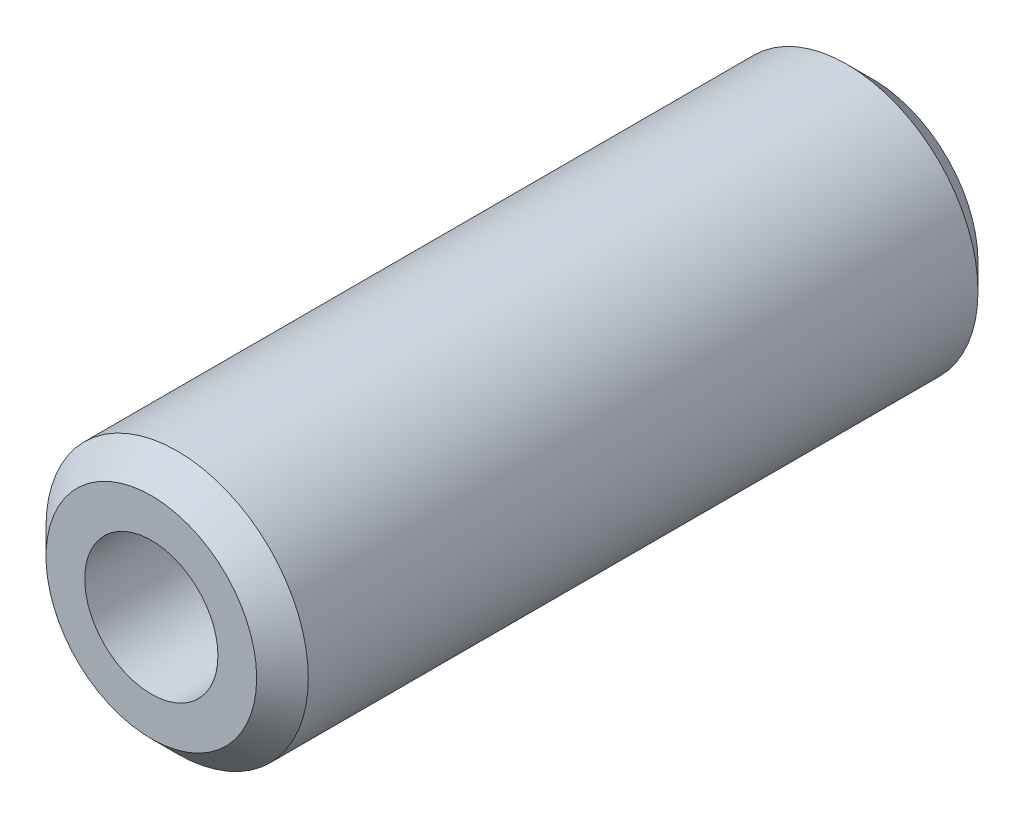
SolidWorks part; units mm, degrees
ref_plane "Front Plane" through (0, 0, 0) normal (0, 0, 1) x (1, 0, 0)
ref_plane "Top Plane" through (0, 0, 0) normal (0, 1, 0) x (1, 0, 0)
ref_plane "Right Plane" through (0, 0, 0) normal (1, 0, 0) x (0, 0, -1)
sketch "Sketch1" plane through (0, 0, 0) normal (0, 0, 1) x (1, 0, 0)
  circle A0 centre (0, 0) radius 12.7
extrude "Boss-Extrude1" add sketch "Sketch1" along normal blind 69.85
sketch "Sketch2" plane through (0, 0, 69.85) normal (0, 0, 1) x (1, 0, 0)
  circle A0 centre (0, 0) radius 6.45
extrude "Cut-Extrude1" cut sketch "Sketch2" against normal through all and the other way through all
chamfer "Chamfer1" distance 2.5 angle 45 2 edges at (12.7, 0, 0) (12.7, 0, 69.85)
